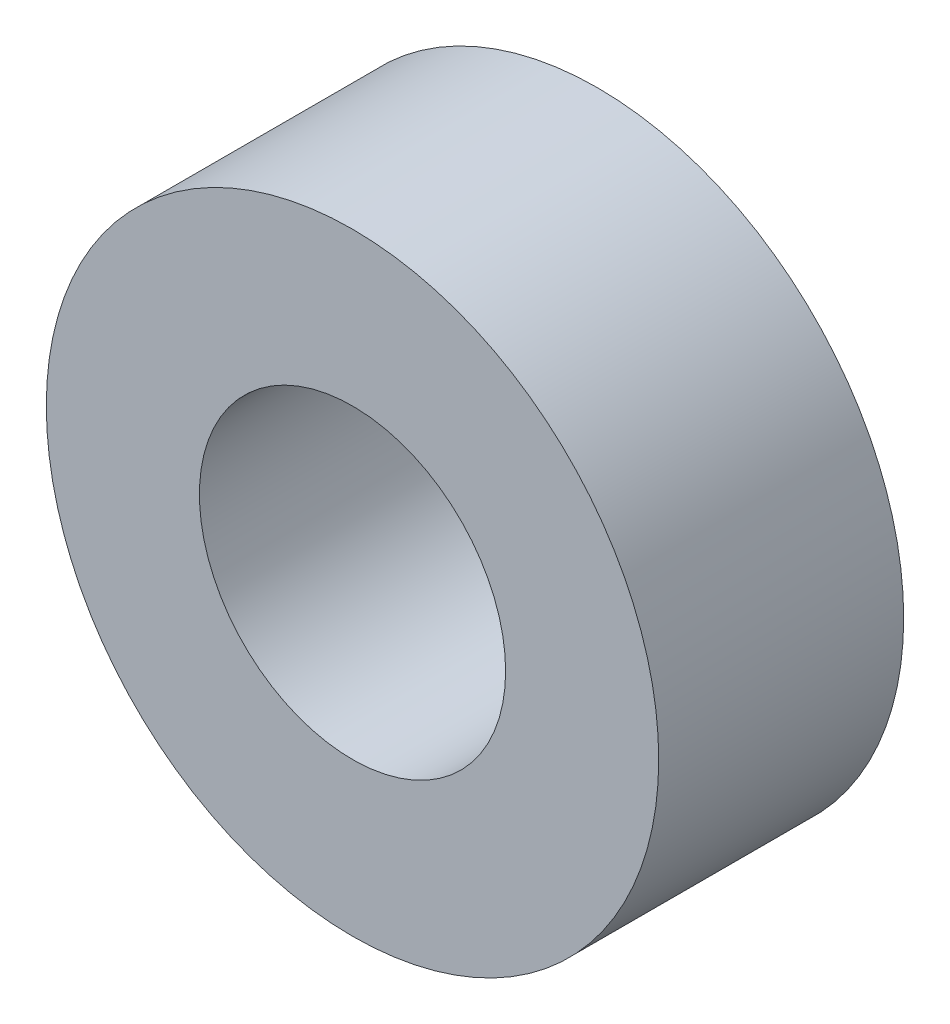
SolidWorks part; units mm, degrees
material "1060 Alloy"
ref_plane "Front Plane" through (0, 0, 0) normal (0, 0, 1) x (1, 0, 0)
ref_plane "Top Plane" through (0, 0, 0) normal (0, 1, 0) x (1, 0, 0)
ref_plane "Right Plane" through (0, 0, 0) normal (1, 0, 0) x (0, 0, -1)
sketch "Sketch1" plane through (0, 0, 0) normal (0, 0, 1) x (1, 0, 0)
  circle A0 centre (0, 0) radius 2.5
  circle A1 centre (0, 0) radius 5
  dimension "D1" = 5
  dimension "D2" = 10
extrude "Boss-Extrude1" add sketch "Sketch1" along normal mid plane 4
